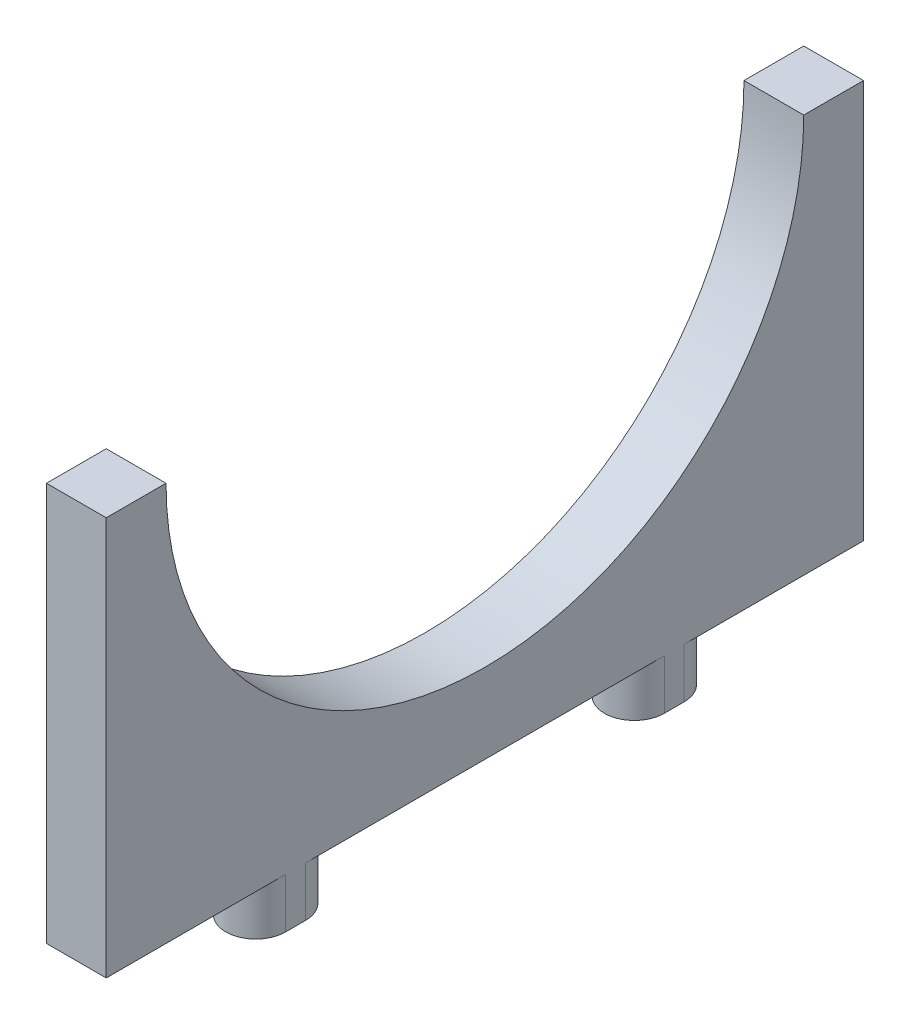
SolidWorks part; units mm, degrees
ref_plane "Front Plane" through (0, 0, 0) normal (0, 0, 1) x (1, 0, 0)
ref_plane "Top Plane" through (0, 0, 0) normal (0, 1, 0) x (1, 0, 0)
ref_plane "Right Plane" through (0, 0, 0) normal (1, 0, 0) x (0, 0, -1)
sketch "Sketch1" plane through (0, 0, 0) normal (1, 0, 0) x (0, 0, -1)
  line L0 (55, 0) -> (-55, 0) construction
  line L1 (-38, 0) -> (-32, 0)
  line L2 (-38, 0) -> (-38, -40)
  line L3 (-38, -40) -> (38, -40)
  line L4 (38, 0) -> (38, -40)
  line L5 (32, 0) -> (38, 0)
  arc A0 (-32, 0) -> (32, 0) centre (0, 0) ccw
  dimension "D1" = 64
  dimension "D2" = 6
  dimension "D3" = 40
extrude "Boss-Extrude1" add sketch "Sketch1" along normal blind 6
sketch "Sketch3" plane through (0, -40, 0) normal (0, -1, 0) x (1, 0, 0)
  line L2 (0, 20) -> (0, 18)
  line L4 (6, 20) -> (6, 18)
  line L8 (0, -18) -> (0, -20)
  line L10 (6, -18) -> (6, -20)
  arc A0 (6, 20) -> (0, 20) centre (3, 20) ccw
  arc A1 (0, 18) -> (6, 18) centre (3, 18) ccw
  arc A2 (0, -20) -> (6, -20) centre (3, -20) ccw
  arc A3 (6, -18) -> (0, -18) centre (3, -18) ccw
extrude "Boss-Extrude2" add sketch "Sketch3" along normal blind 5
